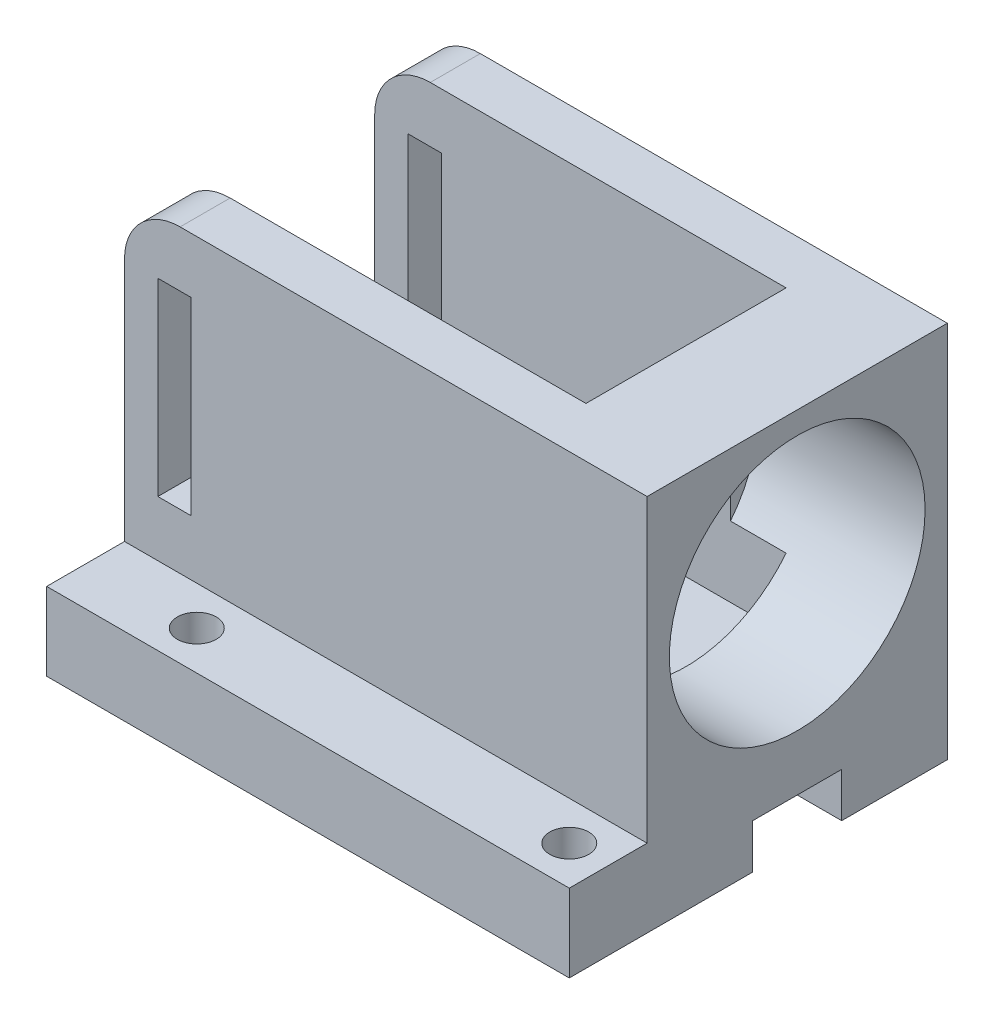
SolidWorks part; units mm, degrees
ref_plane "前视基准面" through (0, 0, 0) normal (0, 0, 1) x (1, 0, 0)
ref_plane "上视基准面" through (0, 0, 0) normal (0, 1, 0) x (1, 0, 0)
ref_plane "右视基准面" through (0, 0, 0) normal (1, 0, 0) x (0, 0, -1)
sketch "草图1" plane through (0, 0, 0) normal (0, 1, 0) x (1, 0, 0)
  line L1 (-23.5, -17) -> (23.5, -17)
  line L2 (-23.5, -17) -> (-23.5, 17)
  line L3 (-23.5, 17) -> (23.5, 17)
  line L4 (23.5, -17) -> (23.5, 17)
  line L5 (-23.5, -17) -> (23.5, 17) construction
  line L6 (-23.5, 17) -> (23.5, -17) construction
  point P0 (0, 0)
  dimension "D1" = 34
  dimension "D2" = 47
extrude "凸台-拉伸1" add sketch "草图1" along normal blind 7
sketch "草图2" plane through (23.5, 0, 0) normal (1, 0, 0) x (0, 0, -1)
  line L0 (-17, 0) -> (3.5, 0)
  line L1 (-17, 0) -> (17, 0) construction
  line L3 (-0.5, -4) -> (7.5, -4)
  line L4 (-0.5, -4) -> (-0.5, 4)
  line L5 (-0.5, 4) -> (7.5, 4)
  line L6 (7.5, -4) -> (7.5, 4)
  line L7 (-0.5, -4) -> (7.5, 4) construction
  line L8 (-0.5, 4) -> (7.5, -4) construction
  line M6 (-17, 0) -> (17, 0)
  dimension "D1" = 20.5
  dimension "D2" = 8
  dimension "D3" = 8
extrude "切除-拉伸1" cut sketch "草图2" against normal through all contours L6 L5 L4 L0 M6
sketch "草图3" plane through (0, 7, 0) normal (0, 1, 0) x (1, 0, 0)
  line L0 (23.5, -17) -> (23.5, 17) construction
  line L1 (-23.5, -17) -> (23.5, -17) construction
  line L2 (20, -13.5) -> (-13.5, -13.5)
  point P0 (20, -13.5)
  dimension "D1" = 3.5
  dimension "D2" = 3.5
  dimension "D3" = 33.5
sketch "草图4" plane through (0, 7, 0) normal (0, 1, 0) x (1, 0, 0)
  point P0 (-13.5, -13.5)
  point P3 (20, -13.5)
hole_wizard "孔1" positions "草图4" profile "草图5" legacy end condition up to next
sketch "草图5" plane through (-13.5, 7, 13.5) normal (1, 0, 0) x (0, 0, 1)
  line L0 (0, 0) -> (0, 7)
  line L1 (0, 7) -> (1.75, 7)
  line L2 (1.75, 7) -> (1.75, 0)
  line L3 (1.75, 0) -> (0, 0)
  line L4 (0, 110) -> (0, -10) construction
  dimension "直径" = 3.5
  dimension "深度" = 7
sketch "草图6" plane through (0, 7, 0) normal (0, 1, 0) x (1, 0, 0)
  line L0 (-23.5, 17) -> (-23.5, -17) construction
  line L1 (23.5, -17) -> (-23.5, -17)
  line L2 (23.5, -17) -> (23.5, -10)
  line L3 (23.5, -10) -> (-23.5, -10)
  line L4 (-23.5, -17) -> (-23.5, -10)
  line L6 (23.5, -10) -> (-23.5, -10)
  line L7 (23.5, -10) -> (23.5, 17)
  line L8 (23.5, 17) -> (-23.5, 17)
  line L9 (-23.5, -10) -> (-23.5, 17)
  line M3 (23.5, -17) -> (23.5, 17)
  line M4 (23.5, 17) -> (-23.5, 17)
  line M5 (-23.5, 17) -> (-23.5, -17)
  dimension "D1" = 7
extrude "凸台-拉伸2" add sketch "草图6" along normal blind 27 contours L3 M3 M4 M5
sketch "草图7" plane through (23.5, 0, 0) normal (1, 0, 0) x (0, 0, -1)
  line L0 (17, 34) -> (17, 0) construction
  line L1 (-10, 34) -> (17, 34)
  line L2 (-10, 34) -> (-10, 7)
  line L3 (-10, 7) -> (17, 7)
  line L4 (17, 34) -> (17, 7)
  line L5 (-10, 7) -> (17, 34)
  line L6 (-10, 34) -> (17, 7)
sketch "草图8" plane through (23.5, 0, 0) normal (1, 0, 0) x (0, 0, -1)
  line L0 (-10, 7) -> (17, 34) construction
  point P0 (3.5, 20.5)
hole_wizard "孔2" positions "草图8" profile "草图9" legacy
sketch "草图9" plane through (23.5, 20.5, -3.5) normal (0, 1, 0) x (0, 0, -1)
  line L0 (0, 0) -> (0, 10)
  line L1 (0, 10) -> (11.5, 10)
  line L2 (11.5, 10) -> (11.5, 0)
  line L3 (11.5, 0) -> (0, 0)
  line L4 (0, 110) -> (0, -10) construction
  dimension "直径" = 23
  dimension "深度" = 10
sketch "草图10" plane through (13.5, 0, 0) normal (1, 0, 0) x (0, 0, -1)
  line L0 (-10, 7) -> (17, 34) construction
  line L1 (-5.5, 34) -> (12.5, 34)
  line L2 (-5.5, 34) -> (-5.5, 7)
  line L3 (-5.5, 7) -> (12.5, 7)
  line L4 (12.5, 34) -> (12.5, 7)
  line L5 (-5.5, 34) -> (12.5, 7) construction
  line L6 (-5.5, 7) -> (12.5, 34) construction
  point P0 (3.5, 20.5)
  dimension "D1" = 27
  dimension "D2" = 18
extrude "切除-拉伸2" cut sketch "草图10" against normal through all
sketch "草图11" plane through (13.5, 0, 0) normal (1, 0, 0) x (0, 0, -1)
  line L0 (-10, 7) -> (17, 34) construction
  circle A0 centre (3.5, 20.5) radius 11.5
extrude "切除-拉伸3" cut sketch "草图11" against normal blind 5
sketch "草图12" plane through (0, 0, 10) normal (0, 0, 1) x (1, 0, 0)
  line L0 (-23.5, 34) -> (-23.5, 7) construction
  line L1 (-20.5, 29) -> (-17.5, 29)
  line L2 (-20.5, 29) -> (-20.5, 12)
  line L3 (-20.5, 12) -> (-17.5, 12)
  line L4 (-17.5, 29) -> (-17.5, 12)
  line L5 (-23.5, 7) -> (23.5, 7) construction
  line L6 (23.5, 34) -> (-23.5, 34) construction
  dimension "D1" = 3
  dimension "D2" = 3
  dimension "D3" = 5
  dimension "D4" = 5
extrude "切除-拉伸4" cut sketch "草图12" against normal through all
fillet "圆角1" radius 5 2 edges at (-23.5, 34, 7.75) (-23.5, 34, -14.75)
